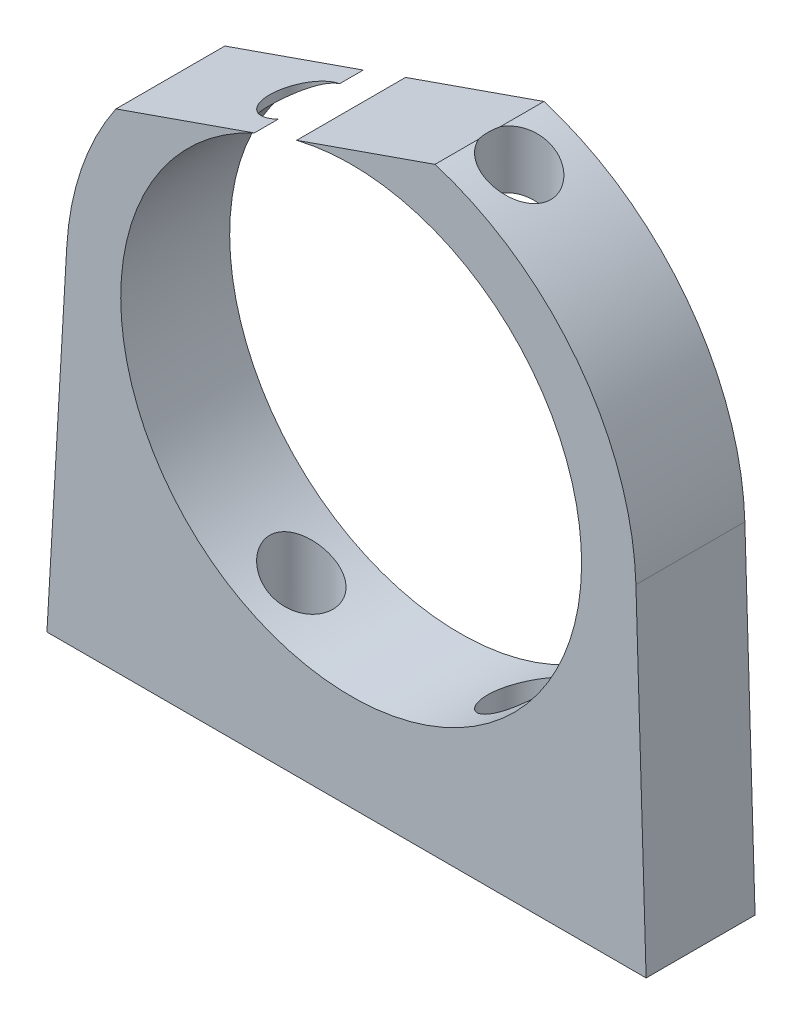
SolidWorks part; units mm, degrees
material "ABS"
ref_plane "前视基准面" through (0, 0, 0) normal (0, 0, 1) x (1, 0, 0)
ref_plane "上视基准面" through (0, 0, 0) normal (0, 1, 0) x (1, 0, 0)
ref_plane "右视基准面" through (0, 0, 0) normal (1, 0, 0) x (0, 0, -1)
other "Configuration Table"
sketch "草图1" plane through (0, 0, 0) normal (0, 0, 1) x (1, 0, 0)
  line L0 (-27.9243, -30) -> (27.0757, -30)
  line L1 (-27.9243, -30) -> (-26.1066, 1.5062)
  line L2 (27.0757, -30) -> (26.1379, 0.796)
  circle A0 centre (0, 0) radius 21.15
  arc A1 (26.1379, 0.796) -> (-26.1066, 1.5062) centre (0, 0) ccw
  circle A2 centre (0, 0) radius 26.15 construction
  point P6 (70.4894, 8.5)
  dimension "D2" = 42.3
  dimension "D1" = 30
  dimension "D4" = 55
  dimension "D5" = 71
  dimension "D6" = 38.5
  dimension "D7" = 43.4137
  dimension "D3" = 5
extrude "凸台-拉伸1" add sketch "草图1" along normal blind 10
sketch "草图2" plane through (0, -30, 0) normal (0, -1, 0) x (1, 0, 0)
  line L0 (-27.9243, 5) -> (27.0757, 5) construction
  line L1 (-27.9243, 10) -> (-27.9243, 0) construction
  line L2 (27.0757, 10) -> (27.0757, 0) construction
  circle A0 centre (10.4257, 5) radius 1.6
  circle A1 centre (-9.5743, 5) radius 1.6
  dimension "D1" = 3.2
  dimension "D2" = 20
  dimension "D3" = 18.35
extrude "切除-拉伸1" cut sketch "草图2" against normal through all
sketch "草图3" plane through (0, -30, 0) normal (0, -1, 0) x (1, 0, 0)
  circle A0 centre (10.4257, 5) radius 2.9
  circle A1 centre (-9.5743, 5) radius 2.9
  dimension "D1" = 5.8
extrude "切除-拉伸2" cut sketch "草图3" against normal through all from offset 5 offset against normal yes
sketch "草图4" plane through (0, 0, 0) normal (0, 0, -1) x (-1, 0, 0)
  line L0 (66.7868, -0.9399) -> (73.3861, 17.9399) construction
  line L1 (66.7868, -0.9399) -> (-39.9099, 36.355) construction
  line L2 (73.3861, 17.9399) -> (-33.3106, 55.2349) construction
  line L3 (-39.9099, 36.355) -> (-33.3106, 55.2349) construction
  line L4 (-7.5385, 25.0398) -> (21.496, 14.8911) construction
  line L5 (-7.859, 25.0459) -> (21.7505, 14.6962)
  line L6 (27.9243, -30) -> (-27.0757, -30) construction
  circle A0 centre (0, 0) radius 21.15 construction
  circle A1 centre (0, 0) radius 21.15 construction
  circle A2 centre (70.0864, 8.5) radius 10
  arc A3 (-7.5385, 25.0398) -> (21.496, 14.8911) centre (0, 0) cw construction
  arc A4 (26.1066, 1.5062) -> (-26.1379, 0.796) centre (0, 0) ccw construction
  arc A5 (-7.859, 25.0459) -> (21.7505, 14.6962) centre (0, 0) cw
  dimension "D1" = 70.6
  dimension "D3" = 20
  dimension "D2" = 38.5
  dimension "D5" = 19.267
  dimension "D4" = 0.1
extrude "切除-拉伸5" cut sketch "草图4" against normal through all contours A5 L5
